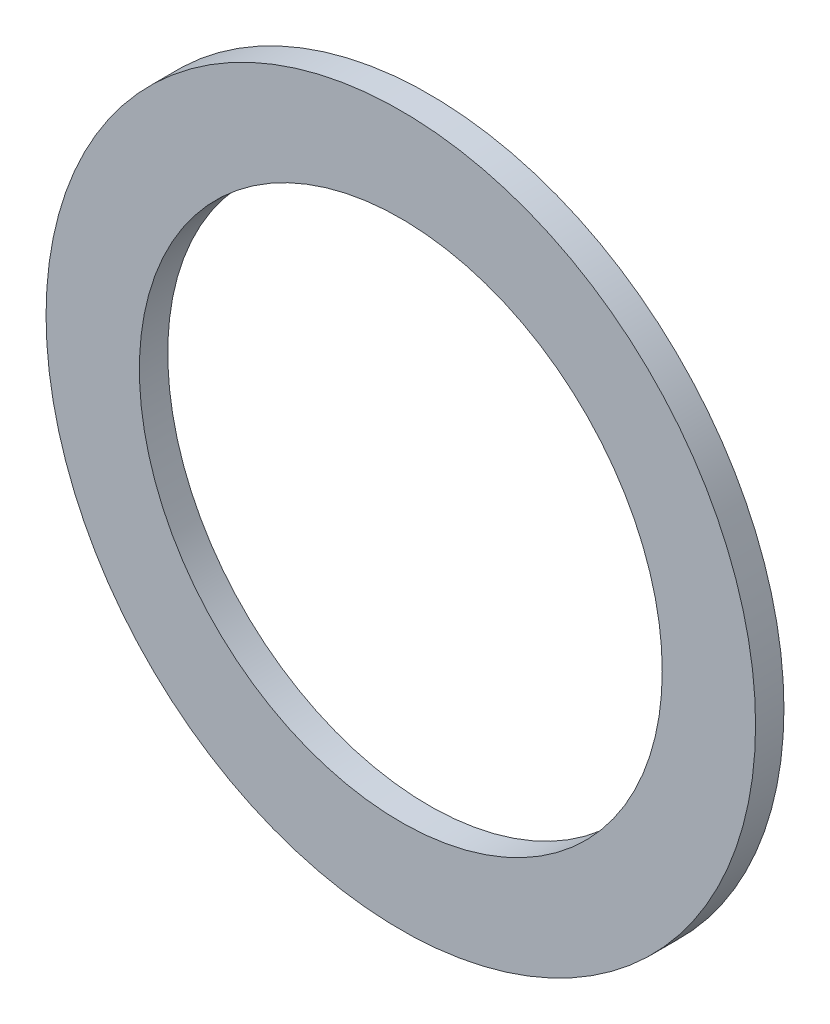
SolidWorks part; units mm, degrees
ref_plane "Plan1" through (0, 0, 0) normal (0, 0, 1) x (1, 0, 0)
ref_plane "Plan2" through (0, 0, 0) normal (0, 1, 0) x (1, 0, 0)
ref_plane "Plan3" through (0, 0, 0) normal (1, 0, 0) x (0, 0, -1)
sketch "Esquisse1" plane through (0, 0, 0) normal (0, 0, 1) x (1, 0, 0)
  circle A0 centre (0, 0) radius 16.385
  circle A1 centre (0, 0) radius 20
  dimension "D1" = 40
  dimension "D2" = 32.77
extrude "Base-Extrusion" add sketch "Esquisse1" along normal blind 1.6
sketch "Esquisse3" plane through (0, 0, 1.6) normal (0, 0, 1) x (1, 0, 0)
  line L0 (1.6289, 15.4996) -> (1.3986, 14.8344)
  line L1 (0, 0) -> (-2.9456, 18.598) construction
  line L2 (1.3986, 14.8344) -> (1.1954, 14.6909)
  line L3 (0, 0) -> (0, 14.7395) construction
  line L5 (-5.9142, 13.6762) -> (-5.6766, 13.6025)
  line L6 (-6.3389, 14.2376) -> (-5.9142, 13.6762)
  arc A1 (0.4537, 14.2428) -> (1.4325, 14.9208) centre (0.4855, 15.2423) ccw construction
  arc A2 (1.6289, 15.4996) -> (2.7411, 16.1583) centre (2.5739, 15.1723) cw
  arc A3 (1.1954, 14.6909) -> (-5.6766, 13.6025) centre (0, 0) ccw
  arc A4 (2.7411, 16.1583) -> (-7.6002, 14.5204) centre (0, 0) ccw
  arc A6 (-6.3389, 14.2376) -> (-7.6002, 14.5204) centre (-7.1364, 13.6344) ccw
  dimension "D1" = 1
  dimension "D3" = 16.3891
  dimension "D4" = 14.7395
  dimension "D2" = 9
  dimension "D5" = 0.2488
extrude "Boss.-Extru.5" add sketch "Esquisse3" against normal up to surface (1.6 mm away)
pattern_circular "Répétition circulaire2" count 20 every 18
